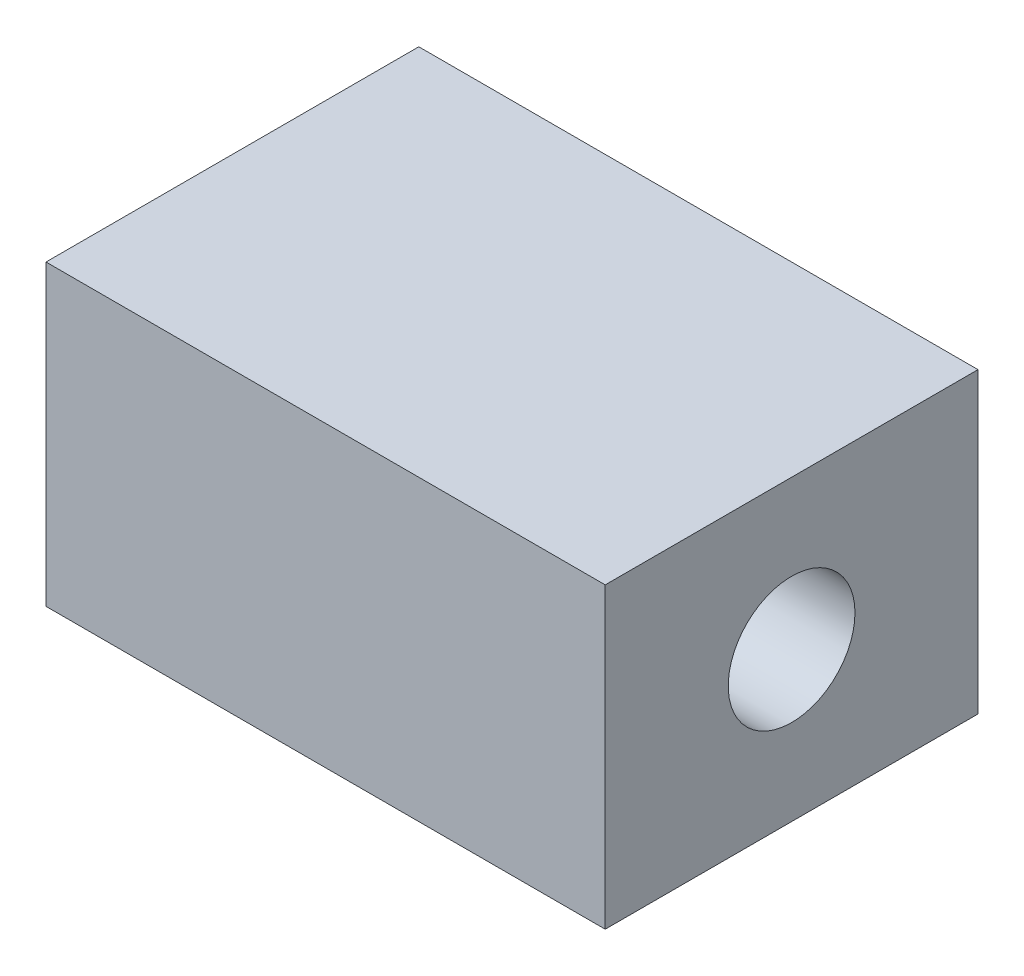
SolidWorks part; units mm, degrees
ref_plane "Front Plane" through (0, 0, 0) normal (0, 0, 1) x (1, 0, 0)
ref_plane "Top Plane" through (0, 0, 0) normal (0, 1, 0) x (1, 0, 0)
ref_plane "Right Plane" through (0, 0, 0) normal (1, 0, 0) x (0, 0, -1)
sketch "Sketch2" plane through (0, 0, 0) normal (0, 1, 0) x (1, 0, 0)
  line L1 (-15, -10) -> (15, -10)
  line L2 (-15, -10) -> (-15, 10)
  line L3 (-15, 10) -> (15, 10)
  line L4 (15, -10) -> (15, 10)
  line L5 (-15, -10) -> (15, 10) construction
  line L6 (-15, 10) -> (15, -10) construction
  point P0 (0, 0)
  dimension "D1" = 30
  dimension "D2" = 20
extrude "Boss-Extrude1" add sketch "Sketch2" along normal mid plane 16
sketch "Sketch5" plane through (0, 0, 0) normal (1, 0, 0) x (0, 0, -1)
  circle A0 centre (0, 0) radius 3.4
  dimension "D1" = 6.8
extrude "Cut-Extrude1" cut sketch "Sketch5" against normal through all both and the other way through all
